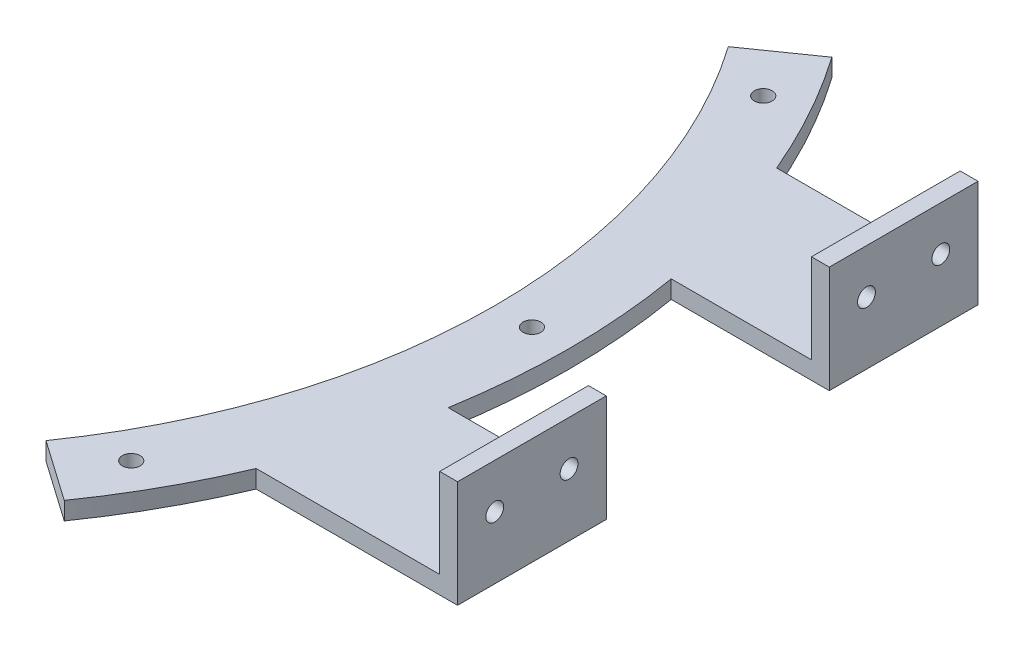
SolidWorks part; units mm, degrees
ref_plane "Front Plane" through (0, 0, 0) normal (0, 0, 1) x (1, 0, 0)
ref_plane "Top Plane" through (0, 0, 0) normal (0, 1, 0) x (1, 0, 0)
ref_plane "Right Plane" through (0, 0, 0) normal (1, 0, 0) x (0, 0, -1)
sketch "Sketch1" plane through (0, 0, 0) normal (0, 1, 0) x (1, 0, 0)
  line L0 (0, 0) -> (450, 0) construction
  line L1 (0, 0) -> (389.7114, 225) construction
  line L2 (0, 0) -> (389.7114, -225) construction
  line L3 (389.7114, 225) -> (389.7114, -225) construction
  line L5 (368.6184, 258.1094) -> (368.6184, -258.1094) construction
  line L11 (550, 175) -> (550, 75)
  line L12 (550, 75) -> (443.706, 75)
  line L13 (550, -175) -> (550, -75)
  line L14 (550, -75) -> (443.706, -75)
  line L15 (0, 0) -> (368.6184, 258.1094) construction
  line L16 (0, 0) -> (368.6184, -258.1094) construction
  line L17 (327.6608, 229.4306) -> (368.6184, 258.1094)
  line L18 (327.6608, -229.4306) -> (368.6184, -258.1094)
  line L19 (550, 175) -> (414.5781, 175)
  line L20 (550, -175) -> (414.5781, -175)
  arc A0 (327.6608, -229.4306) -> (327.6608, 229.4306) centre (0, 0) ccw
  arc A1 (368.6184, -258.1094) -> (368.6184, 258.1094) centre (0, 0) ccw construction
  circle A2 centre (0, 0) radius 425 construction
  circle A3 centre (368.0608, -212.5) radius 6
  circle A4 centre (425, 0) radius 6
  circle A5 centre (368.0608, 212.5) radius 6
  arc A6 (368.6184, -258.1094) -> (414.5781, -175) centre (0, 0) ccw
  arc A7 (414.5781, 175) -> (368.6184, 258.1094) centre (0, 0) ccw
  arc A8 (443.706, -75) -> (443.706, 75) centre (0, 0) ccw
  dimension "D4" = 850
  dimension "D1" = 900
  dimension "D2" = 800
  dimension "D5" = 12
  dimension "D3" = 60
  dimension "D6" = 100
  dimension "D7" = 100
  dimension "D8" = 550
  dimension "D9" = 70
  dimension "D10" = 350
extrude "Boss-Extrude2" add sketch "Sketch1" along normal blind 12
sketch "Sketch2" plane through (0, 12, 0) normal (0, 1, 0) x (1, 0, 0)
  line L4 (550, 75) -> (550, 175)
  line L5 (550, 75) -> (538, 75)
  line L6 (550, 175) -> (538, 175)
  line L7 (538, 75) -> (538, 175)
  line L8 (550, 175) -> (414.5781, 175) construction
  line L11 (550, -175) -> (550, -75)
  line L12 (550, -175) -> (538, -175)
  line L13 (550, -75) -> (538, -75)
  line L14 (538, -175) -> (538, -75)
  line L15 (550, -75) -> (443.706, -75) construction
  line L16 (550, -175) -> (550, -75) construction
  dimension "D1" = 12
extrude "Boss-Extrude3" add sketch "Sketch2" along normal blind 60
sketch "Sketch3" plane through (538, 0, 0) normal (-1, 0, 0) x (0, 0, 1)
  line L0 (-175, 42) -> (-75, 42) construction
  line L1 (-175, 72) -> (-175, 12) construction
  line L2 (-75, 72) -> (-75, 12) construction
  line L3 (75, 42) -> (175, 42) construction
  line L4 (75, 72) -> (75, 12) construction
  line L5 (175, 72) -> (175, 12) construction
  line L7 (-125, 72) -> (-125, 12) construction
  line L8 (-175, 72) -> (-75, 72) construction
  line L9 (-175, 12) -> (-75, 12) construction
  line L10 (125, 12) -> (125, 72) construction
  line L11 (75, 12) -> (175, 12) construction
  line L12 (75, 72) -> (175, 72) construction
  circle A0 centre (-150, 42) radius 6
  circle A1 centre (-100, 42) radius 6
  circle A2 centre (100, 42) radius 6
  circle A3 centre (150, 42) radius 6
  dimension "D1" = 12
  dimension "D2" = 25
  dimension "D3" = 25
  dimension "D4" = 25
  dimension "D5" = 25
extrude "Cut-Extrude1" cut sketch "Sketch3" against normal through all
equation "\"mbtOD\" = 500"
equation "\"mbtT\" = 6"
equation "\"mbtL\" = 3000"
equation "\"mbtFlangeOD\" = 650"
equation "\"mbtFlangeT\" = 12"
equation "\"mbtFlangeBoltCircleDia\" = 650"
equation "\"mbtFlangeHoleDia\" = 12"
equation "\"mbtOringSize\" = 10 "
equation "\"mbtOringDia\" = 620"
equation "\"mbtWidth\" = 2250"
equation "\"skiWidth\" = 1250"
equation "\"mbtCapL\" = 500"
equation "\"vbtRearOD\" = 800"
equation "\"vbtRearT\" = 6.25"
equation "\"vbtRearFlangeOD\" = 900"
equation "\"vbtRearFlangeT\" = 12"
equation "\"vbtRearBoltHoleDia\" = 12"
equation "\"vbtFrontOD\" = 440"
equation "\"vbtFrontT\" = 25"
equation "\"vbtFrontFlangeOD\" = 510"
equation "\"vbtFrontFlangeT\" = 12"
equation "\"vbtFrontBoltHoleDia\" = 12"
equation "\"D4@Sketch1\"=(\"vbtRearOD\"+\"vbtRearFlangeOD\")/2"
equation "\"D1@Sketch1\"=\"vbtRearFlangeOD\""
equation "\"D2@Sketch1\"=\"vbtRearOD\""
equation "\"D5@Sketch1\"=\"vbtRearBoltHoleDia\""
equation "\"D8@Sketch1\"=\"vbtRearFlangeOD\"/2+100mm"
equation "\"D1@Boss-Extrude2\"=\"vbtRearFlangeT\""
equation "\"D1@Sketch2\"=\"vbtRearFlangeT\""
